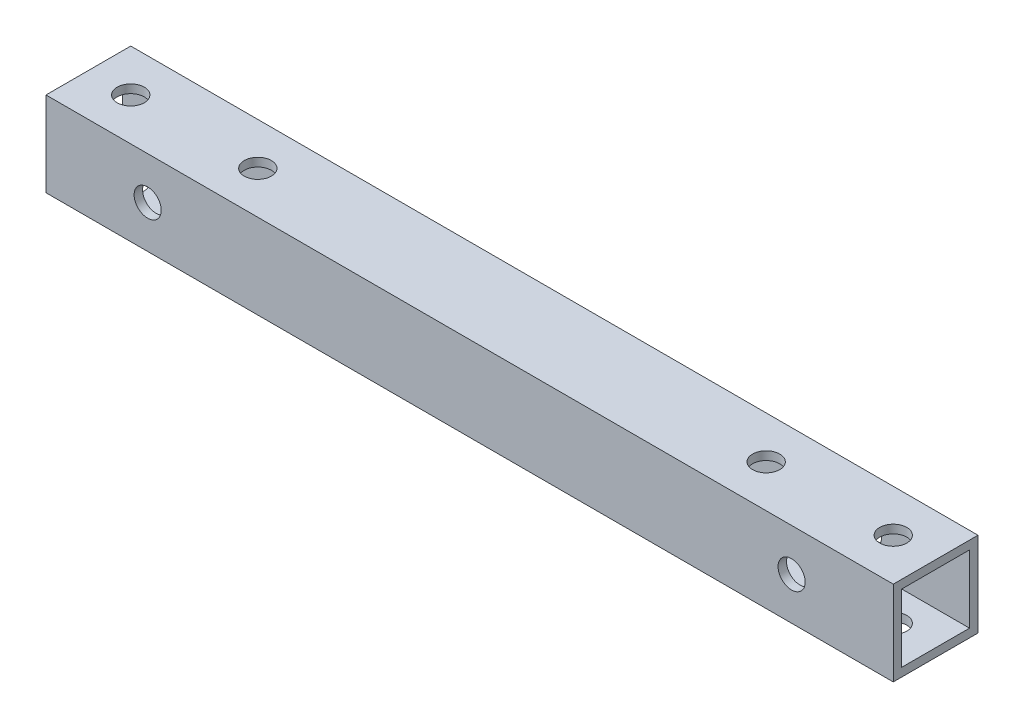
SolidWorks part; units mm, degrees
material "5052-O"
ref_plane "正面" through (0, 0, 0) normal (0, 0, 1) x (1, 0, 0)
ref_plane "平面" through (0, 0, 0) normal (0, 1, 0) x (1, 0, 0)
ref_plane "右側面" through (0, 0, 0) normal (1, 0, 0) x (0, 0, -1)
sketch "ｽｹｯﾁ1" plane through (0, 0, 0) normal (1, 0, 0) x (0, 0, -1)
  line L1 (-5, 5) -> (5, 5)
  line L2 (-5, 5) -> (-5, -5)
  line L3 (-5, -5) -> (5, -5)
  line L4 (5, 5) -> (5, -5)
  line L5 (-5, 5) -> (5, -5) construction
  line L6 (-5, -5) -> (5, 5) construction
  point P0 (0, 0)
  dimension "D1" = 10
  dimension "D2" = 10
extrude "ﾎﾞｽ - 押し出し1" add sketch "ｽｹｯﾁ1" along normal mid plane 100
sketch "ｽｹｯﾁ2" plane through (50, 0, 0) normal (1, 0, 0) x (0, 0, -1)
  line L0 (5, 5) -> (-5, 5) construction
  line L1 (-4, 4) -> (4, 4)
  line L2 (-4, 4) -> (-4, -4)
  line L3 (-4, -4) -> (4, -4)
  line L4 (4, 4) -> (4, -4)
  line L5 (-4, 4) -> (4, -4) construction
  line L6 (-4, -4) -> (4, 4) construction
  line L7 (5, -5) -> (5, 5) construction
  point P0 (0, 0)
  dimension "D1" = 1
  dimension "D2" = 1
extrude "ｶｯﾄ - 押し出し1" cut sketch "ｽｹｯﾁ2" against normal through all
sketch "ｽｹｯﾁ3" plane through (0, 5, 0) normal (0, 1, 0) x (1, 0, 0)
  line L0 (50, 5) -> (-50, 5) construction
  line L1 (-50, 5) -> (-50, -5) construction
  line L2 (0, -5.5) -> (0, 5.5) construction
  circle A0 centre (-45, 0) radius 1.6
  circle A1 centre (-30, 0) radius 1.6
  circle A2 centre (30, 0) radius 1.6
  circle A3 centre (45, 0) radius 1.6
  dimension "D1" = 3.2
  dimension "D2" = 5
  dimension "D3" = 5
  dimension "D4" = 2
extrude "ｶｯﾄ - 押し出し2" cut sketch "ｽｹｯﾁ3" against normal through all
sketch "ｽｹｯﾁ4" plane through (0, 0, 5) normal (0, 0, 1) x (1, 0, 0)
  line L0 (50, 5) -> (-50, 5) construction
  line L1 (-50, 5) -> (-50, -5) construction
  line L2 (0, -5.5) -> (0, 5.5) construction
  circle A0 centre (-38, 0) radius 1.6
  circle A1 centre (38, 0) radius 1.6
  dimension "D1" = 3.2
  dimension "D2" = 5
  dimension "D3" = 12
extrude "ｶｯﾄ - 押し出し3" cut sketch "ｽｹｯﾁ4" against normal through all
